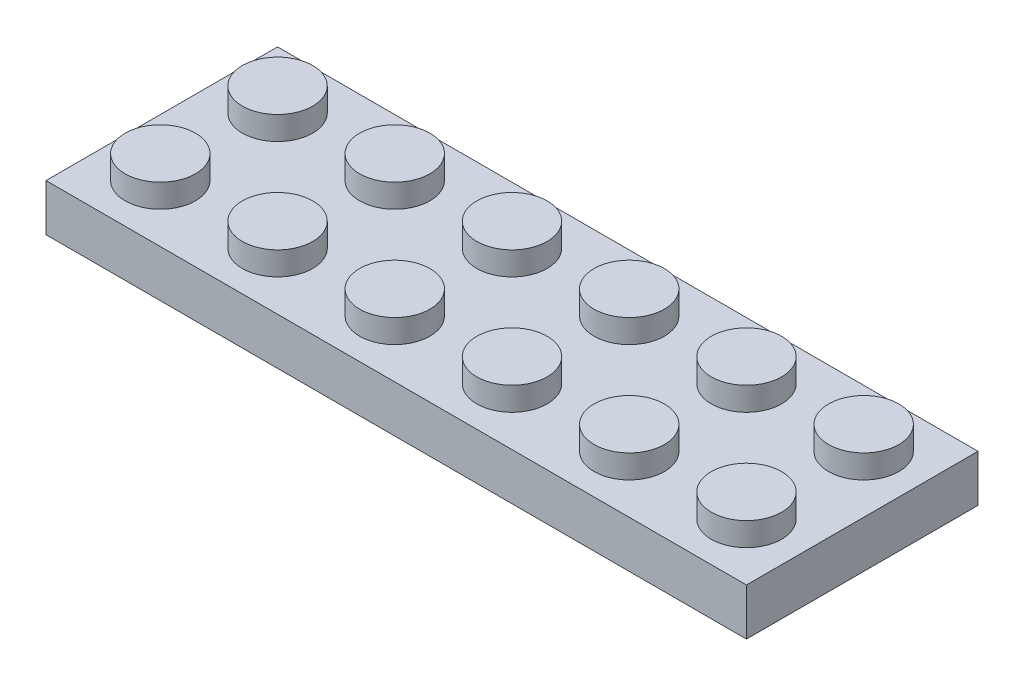
SolidWorks part; units mm, degrees
material "ABS"
ref_plane "Front Plane" through (0, 0, 0) normal (0, 0, 1) x (1, 0, 0)
ref_plane "Top Plane" through (0, 0, 0) normal (0, 1, 0) x (1, 0, 0)
ref_plane "Right Plane" through (0, 0, 0) normal (1, 0, 0) x (0, 0, -1)
sketch "Sketch1" plane through (0, 0, 0) normal (0, 0, 1) x (1, 0, 0)
  line L1 (0, 0) -> (47.8, 0)
  line L2 (0, 0) -> (0, 3.2)
  line L3 (0, 3.2) -> (47.8, 3.2)
  line L4 (47.8, 0) -> (47.8, 3.2)
  line L5 (0, 0) -> (47.8, 3.2) construction
  line L6 (0, 3.2) -> (47.8, 0) construction
  point P4 (23.9, 1.6)
  dimension "D1" = 47.8
  dimension "D2" = 3.2
extrude "Boss-Extrude1" add sketch "Sketch1" against normal blind 15.8
sketch "Sketch2" plane through (0, 3.2, 0) normal (0, 1, 0) x (1, 0, 0)
  line L0 (47.8, 0) -> (0, 0) construction
  circle A0 centre (3.9, 3.9) radius 2.4
  dimension "D1" = 4.8
  dimension "D2" = 3.9
  dimension "D3" = 3.9
extrude "Boss-Extrude2" add sketch "Sketch2" along normal blind 1.6
pattern_linear "LPattern1" count 2 spacing 8 along (0, 0, -1) count 6 spacing 8 along (1, 0, 0) of "Boss-Extrude2"
shell "Shell1" thickness 1.2
sketch "Sketch4" plane through (0, 2, 0) normal (0, -1, 0) x (1, 0, 0)
  line L0 (0, -15.8) -> (0, 0) construction
  line L1 (0, 0) -> (47.8, 0) construction
  circle A0 centre (7.9, -7.9) radius 3.25
  circle A1 centre (7.9, -7.9) radius 2.4
  dimension "D1" = 4.8
  dimension "D2" = 6.5
  dimension "D3" = 7.9
  dimension "D4" = 7.9
extrude "Boss-Extrude3" add sketch "Sketch4" along normal offset from surface (1.8 mm away) 0.2 up to face at (23.9, 0, -7.9)
pattern_linear "LPattern2" count 5 spacing 8 along (1, 0, 0) of "Boss-Extrude3"
